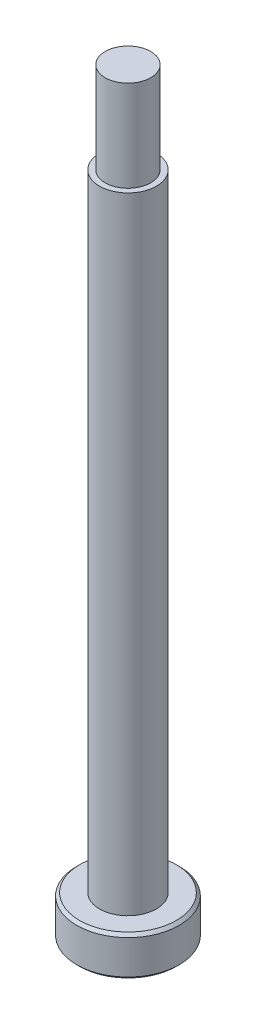
SolidWorks part; units mm, degrees
material "AISI 304"
ref_plane "前视基准面" through (0, 0, 0) normal (0, 0, 1) x (1, 0, 0)
ref_plane "上视基准面" through (0, 0, 0) normal (0, 1, 0) x (1, 0, 0)
ref_plane "右视基准面" through (0, 0, 0) normal (1, 0, 0) x (0, 0, -1)
other "Configuration Table"
sketch "草图1" plane through (0, 0, 0) normal (0, 1, 0) x (1, 0, 0)
  circle A0 centre (0, 0) radius 4.5
  dimension "D1" = 9
extrude "凸台-拉伸1" add sketch "草图1" against normal blind 3.5
sketch "草图2" plane through (0, 0, 0) normal (0, 1, 0) x (1, 0, 0)
  circle A0 centre (0, 0) radius 2.5
  dimension "D1" = 5
extrude "凸台-拉伸2" add sketch "草图2" along normal blind 55
sketch "草图3" plane through (0, 55, 0) normal (0, 1, 0) x (1, 0, 0)
  circle A0 centre (0, 0) radius 2
  dimension "D1" = 4
extrude "凸台-拉伸3" add sketch "草图3" along normal blind 8
sketch "草图4" plane through (0, -3.5, 0) normal (0, -1, 0) x (1, 0, 0)
  line L1 (1.5, -0.866) -> (1.5, 0.866)
  line L2 (1.5, 0.866) -> (0, 1.7321)
  line L3 (0, 1.7321) -> (-1.5, 0.866)
  line L4 (-1.5, 0.866) -> (-1.5, -0.866)
  line L5 (-1.5, -0.866) -> (0, -1.7321)
  line L6 (0, -1.7321) -> (1.5, -0.866)
  circle A0 centre (0, 0) radius 1.5 construction
  dimension "D1" = 3
extrude "切除-拉伸1" cut sketch "草图4" against normal blind 2.5
chamfer "倒角1" distance 0.25 angle 45 2 edges at (0, -3.5, 4.5) (0, 0, 4.5)
